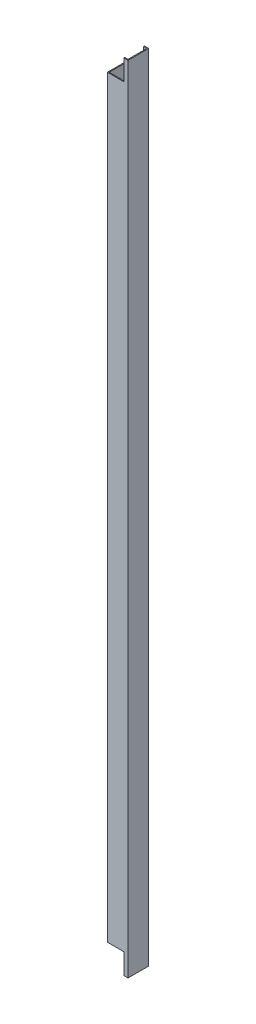
SolidWorks part; units mm, degrees
ref_plane "Front Plane" through (0, 0, 0) normal (0, 0, 1) x (1, 0, 0)
ref_plane "Top Plane" through (0, 0, 0) normal (0, 1, 0) x (1, 0, 0)
ref_plane "Right Plane" through (0, 0, 0) normal (1, 0, 0) x (0, 0, -1)
sketch "Sketch1" plane through (0, 0, 0) normal (0, 1, 0) x (1, 0, 0)
  line L0 (0, 0) -> (0, 50)
  line L1 (0, 50) -> (50, 50)
  line L2 (50, 50) -> (50, 0)
  line L3 (50, 0) -> (0, 0)
  line L4 (2.2, 47.8) -> (47.8, 47.8)
  line L5 (47.8, 47.8) -> (47.8, 2.2)
  line L6 (47.8, 2.2) -> (2.2, 2.2)
  line L7 (2.2, 2.2) -> (2.2, 47.8)
  dimension "D1" = 50
  dimension "D2" = 50
  dimension "D3" = 2.2
extrude "Boss-Extrude1" add sketch "Sketch1" along normal blind 1923
sketch "Sketch2" plane through (0, 0, 0) normal (0, 0, 1) x (1, 0, 0)
  line L0 (0, 0) -> (0, 50)
  line L1 (0, 1923) -> (0, 0) construction
  line L2 (0, 50) -> (40, 50)
  line L3 (40, 50) -> (40, 0)
  line L5 (40, 0) -> (0, 0)
  line L6 (0, 1923) -> (40, 1923)
  line L7 (0, 1923) -> (50, 1923) construction
  line L8 (40, 1923) -> (40, 1873)
  line L9 (40, 1873) -> (0, 1873)
  line L10 (0, 1873) -> (0, 1923)
  dimension "D1" = 50
  dimension "D2" = 40
  dimension "D3" = 50
  dimension "D4" = 40
extrude "Cut-Extrude2" cut sketch "Sketch2" against normal blind 50
equation "\"SquareTube_length\"=1923.0"
equation "\"D1@Boss-Extrude1\"=\"SquareTube_length\""
equation "\"SquareTube_inBack1_cutDepth50_R\"=50"
equation "\"D1@Sketch2\"= \"SquareTube_inBack1_cutDepth50_R\""
equation "\"SquareTube_inBack1_cutDepth50_L\"=50"
equation "\"D3@Sketch2\"=\"SquareTube_inBack1_cutDepth50_L\""
equation "\"CarBeamWidth\"=700.0"
equation "\"MetalSheet_3mm_length\"=5030.0"
equation "\"MetalSheet_3mm_width\"=1923.0"
equation "\"MetalSheet_3mm_FloorCut_L_length\"=1764.0"
equation "\"MetalSheet_3mm_FloorCut_L_disdance\"=1665.0"
equation "\"MetalSheet_3mm_FloorCut_R_length\"=1764.0"
equation "\"MetalSheet_3mm_FloorCut_R_disdance\"=1665.0"
equation "\"indoorHeight\"=1940.0"
equation "\"x\"=66.0"
equation "\"da\"=62.0"
equation "\"SquareTube_wheel_length\"= 750"
equation "\"channelSteel_length\"=5030.0"
equation "\"SquareTube_inFront1_cutDepth50_R\"=0.5"
equation "\"SquareTube_inFront1_cutDepth50_L\"=0.5"
equation "\"SquareTube_inFront2_cutDepth50_R\"=0.5"
equation "\"SquareTube_inFront2_cutDepth50_L\"=0.5"
equation "\"SquareTube_inFront3_cutDepth50_R\"=0.5"
equation "\"SquareTube_inFront3_cutDepth50_L\"=0.5"
equation "\"SquareTube_inFront4_cutDepth50_R\"=0.5"
equation "\"SquareTube_inFront4_cutDepth50_L\"=0.5"
equation "\"SquareTube_inFront5_cutDepth50_R\"=50"
equation "\"SquareTube_inFront5_cutDepth50_L\"=50"
equation "\"SquareTube_inFront6_cutDepth50_R\"=50"
equation "\"SquareTube_inFront6_cutDepth50_L\"=50"
equation "\"SquareTube_inFront7_cutDepth50_R\"=50"
equation "\"SquareTube_inFront7_cutDepth50_L\"=50"
equation "\"SquareTube_inFront8_cutDepth50_R\"=50"
equation "\"SquareTube_inFront8_cutDepth50_L\"=50"
equation "\"SquareTube_inFront9_cutDepth50_R\"=50"
equation "\"SquareTube_inFront9_cutDepth50_L\"=50"
equation "\"SquareTube_inFront10_cutDepth50_R\"=50"
equation "\"SquareTube_inFront10_cutDepth50_L\"=50"
equation "\"SquareTube_inBack2_cutDepth50_R\"=50"
equation "\"SquareTube_inBack2_cutDepth50_L\"=50"
equation "\"SquareTube_inBack3_cutDepth50_R\"=50"
equation "\"SquareTube_inBack3_cutDepth50_L\"=50"
equation "\"SquareTube_inBack4_cutDepth50_R\"=50"
equation "\"SquareTube_inBack4_cutDepth50_L\"=50"
equation "\"SquareTube_inBack5_cutDepth50_R\"=50"
equation "\"SquareTube_inBack5_cutDepth50_L\"=50"
equation "\"SquareTube_inBack6_cutDepth50_R\"=0.5"
equation "\"SquareTube_inBack6_cutDepth50_L\"=0.5"
equation "\"SquareTube_inFront11_cutDepth50_R\"=50"
equation "\"SquareTube_inFront11_cutDepth50_L\"=50"
equation "\"SquareTube_inFront12_cutDepth50_R\"=50"
equation "\"SquareTube_inFront12_cutDepth50_L\"=50"
equation "\"SquareTube_inFront13_cutDepth50_R\"=50"
equation "\"SquareTube_inFront13_cutDepth50_L\"=50"
equation "\"SquareTube_inFront14_cutDepth50_R\"=50"
equation "\"SquareTube_inFront14_cutDepth50_L\"=50"
equation "\"SquareTube_inBack7_cutDepth50_R\"=0.5"
equation "\"SquareTube_inBack7_cutDepth50_L\"=0.5"
equation "\"SquareTube_inBack8_cutDepth50_R\"=0.5"
equation "\"SquareTube_inBack8_cutDepth50_L\"=0.5"
